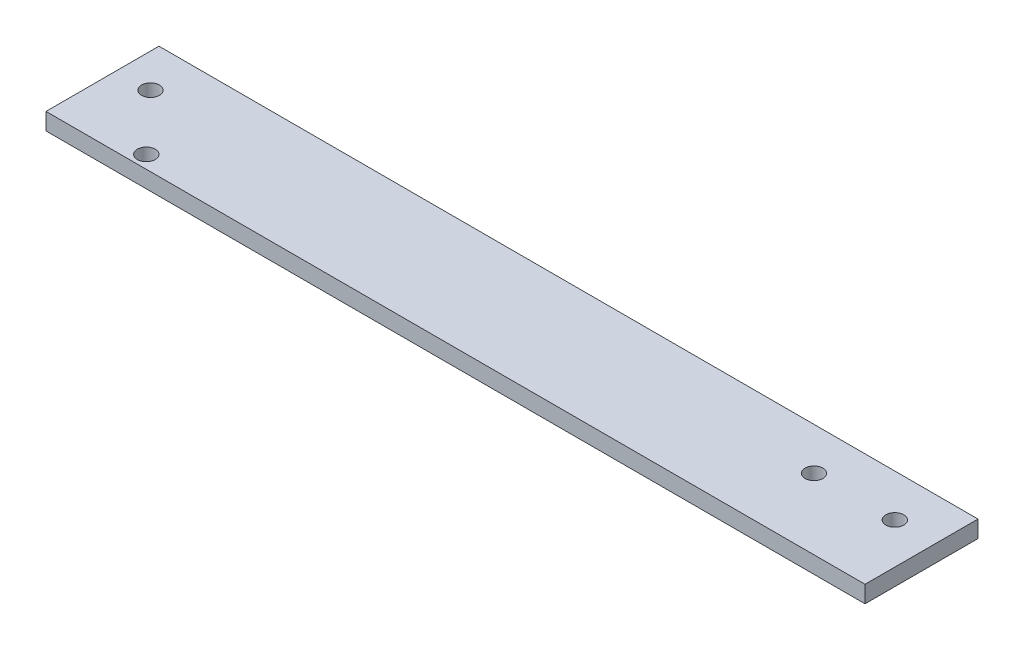
SolidWorks part; units mm, degrees
ref_plane "Front Plane" through (0, 0, 0) normal (0, 0, 1) x (1, 0, 0)
ref_plane "Top Plane" through (0, 0, 0) normal (0, 1, 0) x (1, 0, 0)
ref_plane "Right Plane" through (0, 0, 0) normal (1, 0, 0) x (0, 0, -1)
sketch "Sketch1" plane through (0, 0, 0) normal (0, 1, 0) x (1, 0, 0)
  line L0 (0, 0) -> (-145, 0)
  line L1 (-145, 0) -> (-145, -20)
  line L2 (-24, -20) -> (0, -20)
  line L3 (0, -20) -> (0, 0)
  line L4 (-145, -20) -> (-24, -20)
extrude "Extrude1" add sketch "Sketch1" along normal blind 3
sketch "Sketch2" plane through (0, 3, 0) normal (0, 1, 0) x (1, 0, 0)
  line L0 (-145, 0) -> (-139, 0) construction
  line L1 (0, 0) -> (-145, 0) construction
  line L2 (-139, 0) -> (-139, -7.5) construction
  line L3 (-139, -7.5) -> (-7.2248, -7.5) construction
  line L4 (-7.2248, -7.5) -> (-7.2248, -99.3583) construction
  circle A0 centre (-139, -7.5) radius 1.5875
  circle A1 centre (-7.2248, -7.5) radius 1.5875
  circle A2 centre (-7.2248, -99.3583) radius 1.5875
extrude "Extrude2" cut sketch "Sketch2" against normal up to surface (3 mm away) up to face at (-72.5, 0, 10)
sketch "Sketch3" plane through (0, 3, 0) normal (0, 1, 0) x (1, 0, 0)
  line L0 (-139, -7.5) -> (-139, -17.71) construction
  line L1 (-139, -17.71) -> (-7.2248, -17.71) construction
  line L2 (-7.2248, -7.5) -> (-7.2248, -17.71) construction
  line L3 (-139, -17.71) -> (-129.53, -17.71) construction
sketch "Sketch4" plane through (0, 3, 0) normal (0, 1, 0) x (1, 0, 0)
  line L0 (-7.2248, -7.5) -> (-21.5348, -7.5) construction
  circle A0 centre (-21.5348, -7.5) radius 1.59
extrude "Extrude3" cut sketch "Sketch4" against normal up to surface (3 mm away) up to face at (-7.2248, 0, 9.0875)
sketch "Sketch5" plane through (0, 3, 0) normal (0, 1, 0) x (1, 0, 0)
  line L0 (-7.2248, -7.5) -> (-21.5348, -7.5) construction
  line L1 (-21.5348, -7.5) -> (-21.5348, -17.71) construction
  line L2 (-139, -17.71) -> (-7.2248, -17.71) construction
  line L3 (-21.5348, -17.71) -> (-129.5348, -17.71) construction
  circle A0 centre (-129.5348, -17.71) radius 1.59
extrude "Extrude5" cut sketch "Sketch5" against normal up to surface (3 mm away) up to face at (-21.5348, 0, 9.09)
